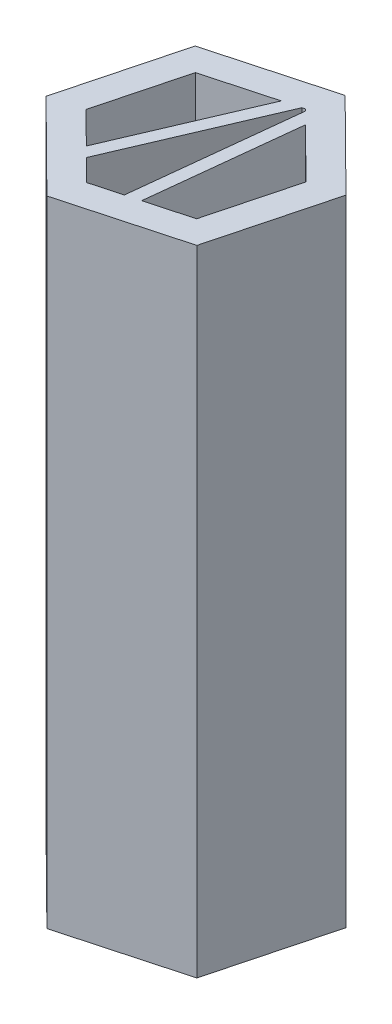
SolidWorks part; units mm, degrees
ref_plane "Front Plane" through (0, 0, 0) normal (0, 0, 1) x (1, 0, 0)
ref_plane "Top Plane" through (0, 0, 0) normal (0, 1, 0) x (1, 0, 0)
ref_plane "Right Plane" through (0, 0, 0) normal (1, 0, 0) x (0, 0, -1)
sketch "Sketch1" plane through (0, 0, 0) normal (0, 1, 0) x (1, 0, 0)
  line L1 (6.1544, -6.0929) -> (8.3538, 2.2834)
  line L2 (8.3538, 2.2834) -> (2.1994, 8.3763)
  line L3 (2.1994, 8.3763) -> (-6.1544, 6.0929)
  line L4 (-6.1544, 6.0929) -> (-8.3538, -2.2834)
  line L5 (-8.3538, -2.2834) -> (-2.1994, -8.3763)
  line L6 (-2.1994, -8.3763) -> (6.1544, -6.0929)
  line L7 (-1.6129, -6.1426) -> (4.5132, -4.4681)
  line L8 (4.5132, -4.4681) -> (6.1261, 1.6745)
  line L9 (6.1261, 1.6745) -> (1.6129, 6.1426)
  line L10 (1.6129, 6.1426) -> (-4.5132, 4.4681)
  line L11 (-4.5132, 4.4681) -> (-6.1261, -1.6745)
  line L12 (-6.1261, -1.6745) -> (-1.6129, -6.1426)
  circle A0 centre (0, 0) radius 7.5 construction
  circle A1 centre (0, 0) radius 5.5 construction
  dimension "D1" = 15
  dimension "D2" = 2
extrude "Boss-Extrude1" add sketch "Sketch1" along normal blind 45
sketch "Sketch2" plane through (0, 45, 0) normal (0, 1, 0) x (1, 0, 0)
  line L0 (-3.8695, -3.9086) -> (0.2743, 5.7767)
  line L1 (-6.1261, -1.6745) -> (-1.6129, -6.1426) construction
  line L2 (1.6129, 6.1426) -> (-4.5132, 4.4681) construction
  line L3 (0.2743, 5.7767) -> (1.42, 6.0899)
  line L4 (1.42, 6.0899) -> (-3.1588, -4.6121)
  line L5 (-3.1588, -4.6121) -> (-3.8695, -3.9086)
  line L6 (1.4502, -5.3054) -> (2.599, 5.1664)
  line L7 (-1.6129, -6.1426) -> (4.5132, -4.4681) construction
  line L8 (6.1261, 1.6745) -> (1.6129, 6.1426) construction
  line L9 (2.599, 5.1664) -> (1.755, 6.0019)
  line L10 (1.755, 6.0019) -> (0.4856, -5.569)
  line L11 (0.4856, -5.569) -> (1.4502, -5.3054)
  dimension "D1" = 0.2
  dimension "D2" = 0.2
  dimension "D3" = 1
  dimension "D4" = 1
extrude "Boss-Extrude2" add sketch "Sketch2" against normal blind 45
